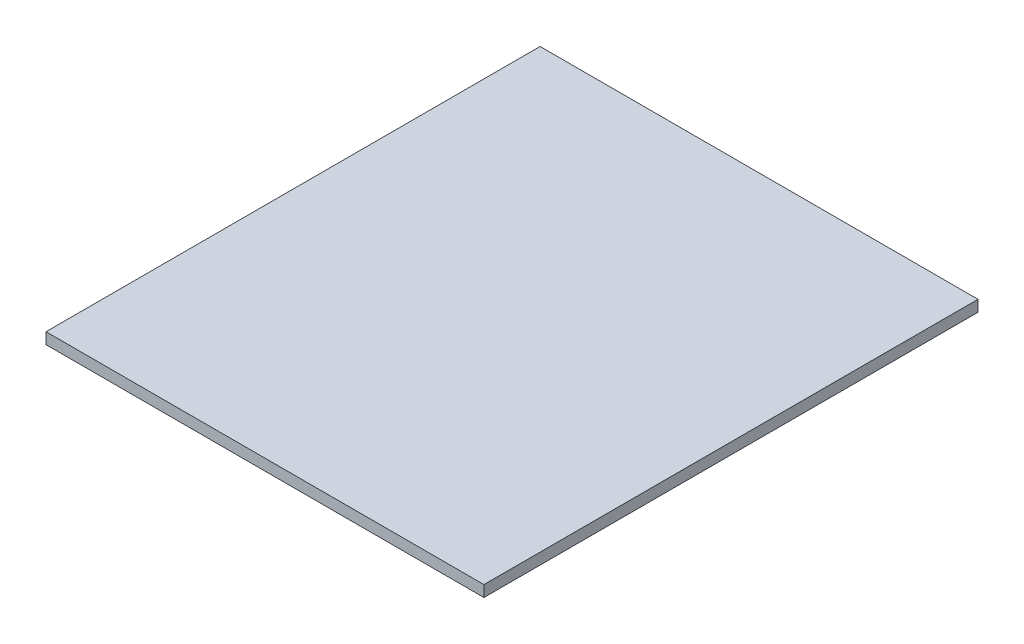
SolidWorks part; units mm, degrees
ref_plane "Front Plane" through (0, 0, 0) normal (0, 0, 1) x (1, 0, 0)
ref_plane "Top Plane" through (0, 0, 0) normal (0, 1, 0) x (1, 0, 0)
ref_plane "Right Plane" through (0, 0, 0) normal (1, 0, 0) x (0, 0, -1)
sketch "Sketch1" plane through (0, 0, 0) normal (0, 1, 0) x (1, 0, 0)
  line L1 (0, 0) -> (78, 0)
  line L2 (0, 0) -> (0, 88)
  line L3 (0, 88) -> (78, 88)
  line L4 (78, 0) -> (78, 88)
  dimension "D1" = 78
  dimension "D2" = 88
extrude "Boss-Extrude1" add sketch "Sketch1" along normal blind 2
